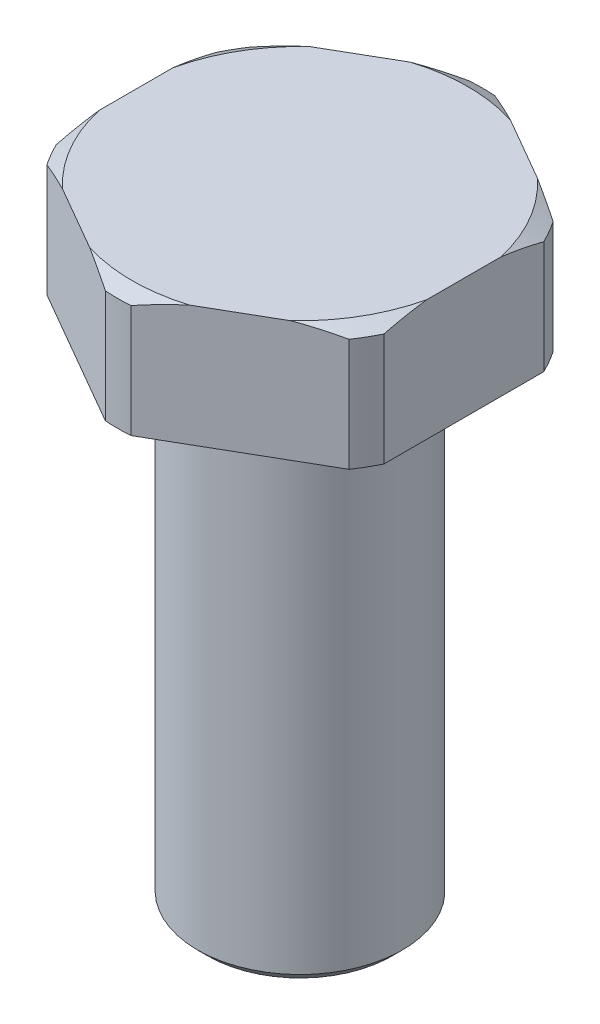
SolidWorks part; units mm, degrees
material "AISI 1020 Stal walcowana na zimno"
ref_plane "Płaszczyzna przednia" through (0, 0, 0) normal (0, 0, 1) x (1, 0, 0)
ref_plane "Płaszczyzna górna" through (0, 0, 0) normal (0, 1, 0) x (1, 0, 0)
ref_plane "Płaszczyzna prawa" through (0, 0, 0) normal (1, 0, 0) x (0, 0, -1)
sketch "Szkic1" plane through (0, 0, 0) normal (0, 0, 1) x (1, 0, 0)
  line L0 (0, 37.2879) -> (0, -37.2879) construction
  line L1 (0, 6.4) -> (8.2, 6.4)
  line L2 (8.9, 5.9959) -> (8.9, 0.5)
  line L3 (8.9, 0.5) -> (7.3, 0.5)
  line L4 (5, 0) -> (5, -23.5)
  line L5 (4.5, -24) -> (0, -24)
  line L6 (7.3, 0.5) -> (7.3, 0)
  line L7 (7.3, 0) -> (5, 0)
  line L8 (5, -23.5) -> (4.5, -24)
  line L9 (0, 6.4) -> (0, -24)
  line L10 (8.2, 6.4) -> (8.9, 5.9959)
  point P4 (8.9, 6.4)
  point P5 (5, -24)
  dimension "D1" = 17.8
  dimension "D2" = 24
  dimension "D3" = 10
  dimension "D4" = 6.4
  dimension "D5" = 0.5
  dimension "D6" = 14.6
  dimension "D7" = 0.7
  dimension "D8" = 30
revolve "Obrót1" add sketch "Szkic1" angle 360 about L0
cosmetic thread "Oznaczenie gwintu1" [suppressed] parameters "D1"=14, "D2"=6.619
cosmetic thread "Oznaczenie gwintu2" parameters "D1"=16, "D2"=8.344
sketch "Szkic2" plane through (0, 6.4, 0) normal (0, 1, 0) x (1, 0, 0)
  line L1 (0, 9.2376) -> (-8, 4.6188)
  line L2 (-8, 4.6188) -> (-8, -4.6188)
  line L3 (-8, -4.6188) -> (0, -9.2376)
  line L4 (0, -9.2376) -> (8, -4.6188)
  line L5 (8, -4.6188) -> (8, 4.6188)
  line L6 (8, 4.6188) -> (0, 9.2376)
  circle A0 centre (0, 0) radius 8 construction
  dimension "D1" = 16
extrude "Wytnij-wyciągnięcie1" cut sketch "Szkic2" against normal up to next (30.4 mm away) flip side to cut
